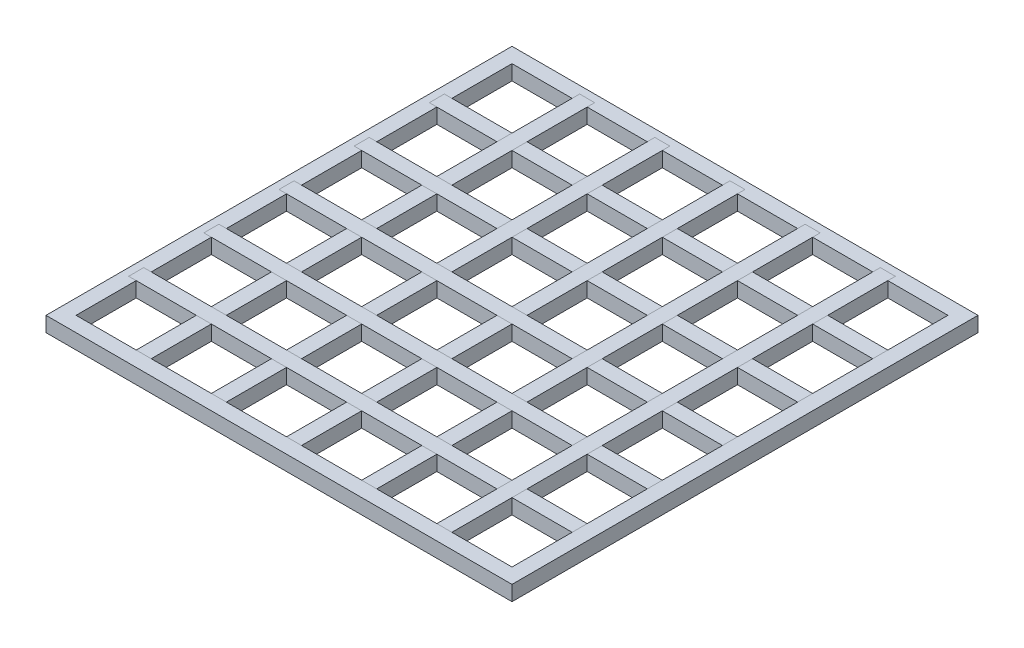
SolidWorks part; units mm, degrees
ref_plane "Front Plane" through (0, 0, 0) normal (0, 0, 1) x (1, 0, 0)
ref_plane "Top Plane" through (0, 0, 0) normal (0, 1, 0) x (1, 0, 0)
ref_plane "Right Plane" through (0, 0, 0) normal (1, 0, 0) x (0, 0, -1)
sketch "Sketch1" plane through (0, 0, 0) normal (0, 1, 0) x (1, 0, 0)
  line L0 (-10, 15) -> (-10, -15)
  line L1 (-15, 15) -> (15, 15)
  line L2 (-15, 15) -> (-15, -15)
  line L3 (-15, -15) -> (15, -15)
  line L4 (15, 15) -> (15, -15)
  line L5 (-15, 15) -> (15, -15) construction
  line L6 (-15, -15) -> (15, 15) construction
  line L7 (-5, 15) -> (-5, -15)
  line L8 (0, 15) -> (0, -15)
  line L9 (5, 15) -> (5, -15)
  line L10 (10, 15) -> (10, -15)
  line L11 (-15, -10) -> (15, -10)
  line L12 (-15, -5) -> (15, -5)
  line L13 (-15, 0) -> (15, 0)
  line L14 (-15, 5) -> (15, 5)
  line L15 (-15, 10) -> (15, 10)
  point P0 (0, 0)
  dimension "D1" = 30
  dimension "D2" = 30
  dimension "D3" = 5
  dimension "D5" = 5
  dimension "D6" = 5
  dimension "D8" = 5
  dimension "D4" = 5
  dimension "D7" = 5
extrude "Extrude-Thin1" add sketch "Sketch1" along normal blind 1 thin thin type mid plane wall 1
equation "\"D3@Sketch1\"=5"
equation "\"D5@Sketch1\"=\"D3@Sketch1\""
equation "\"D8@Sketch1\"=\"D5@Sketch1\""
